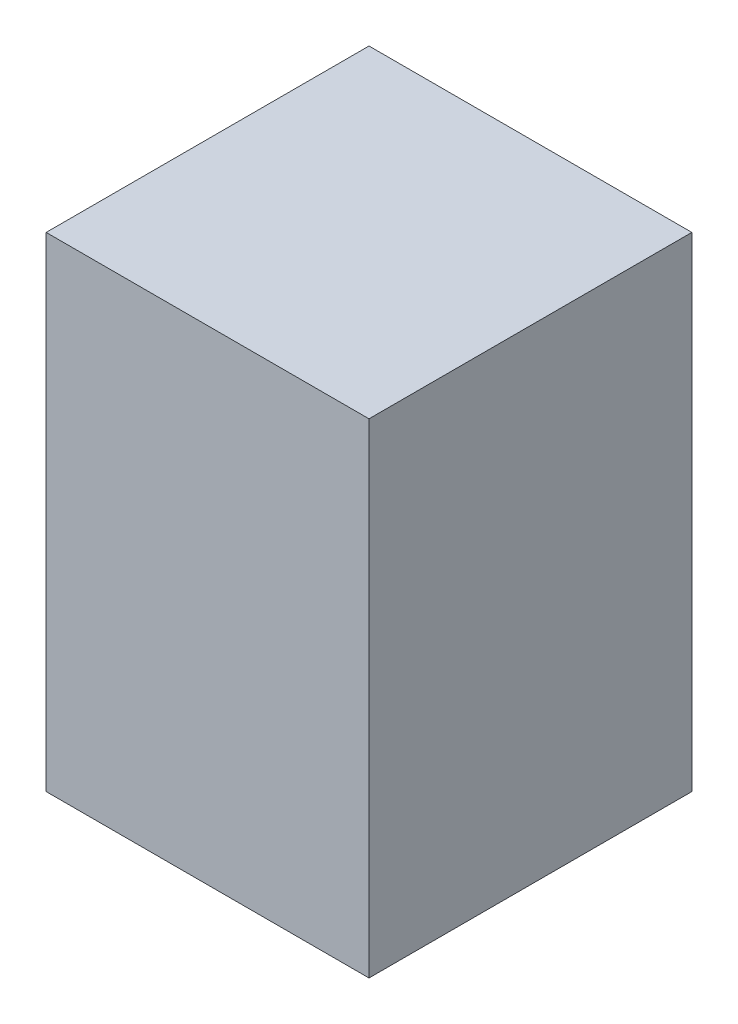
SolidWorks part; units mm, degrees
ref_plane "Front Plane" through (0, 0, 0) normal (0, 0, 1) x (1, 0, 0)
ref_plane "Top Plane" through (0, 0, 0) normal (0, 1, 0) x (1, 0, 0)
ref_plane "Right Plane" through (0, 0, 0) normal (1, 0, 0) x (0, 0, -1)
other "Configuration Table"
sketch "Sketch1" plane through (0, 0, 0) normal (0, 0, 1) x (1, 0, 0)
  line L1 (60, 0) -> (140, 0)
  line L2 (60, 0) -> (60, 120)
  line L3 (60, 120) -> (140, 120)
  line L4 (140, 0) -> (140, 120)
extrude "STORE_ayak_3_1" add sketch "Sketch1" against normal blind 80 from offset 680 separate body
